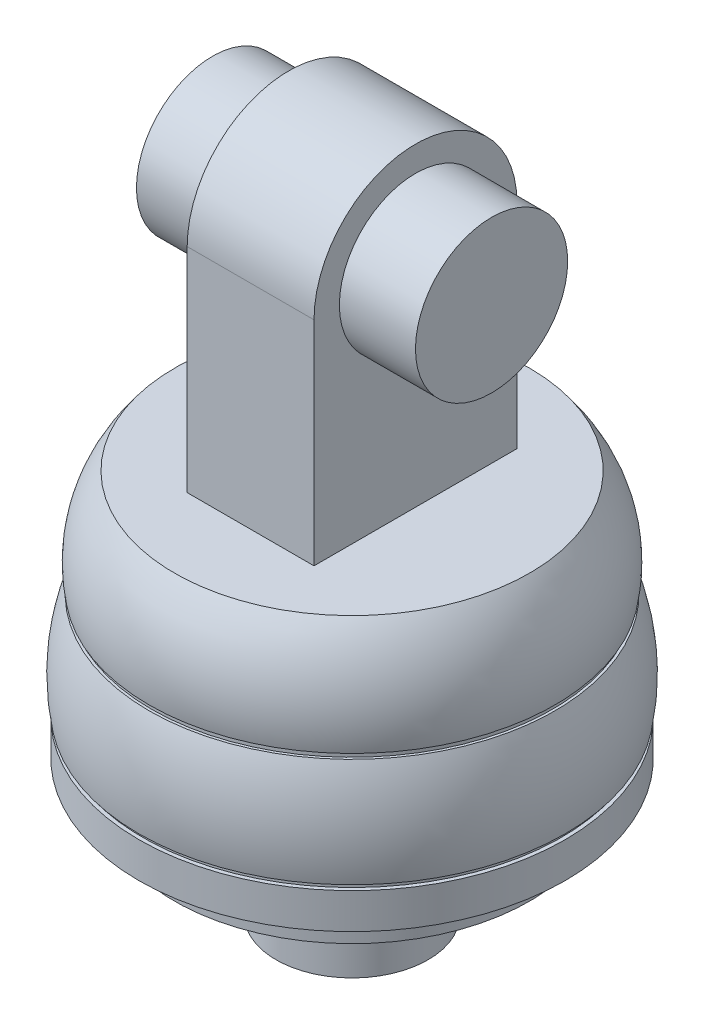
SolidWorks part; units mm, degrees
ref_plane "Front Plane" through (0, 0, 0) normal (0, 0, 1) x (1, 0, 0)
ref_plane "Top Plane" through (0, 0, 0) normal (0, 1, 0) x (1, 0, 0)
ref_plane "Right Plane" through (0, 0, 0) normal (1, 0, 0) x (0, 0, -1)
sketch "Sketch1" plane through (0, 0, 0) normal (0, 0, 1) x (1, 0, 0)
  line L0 (0, 0) -> (0, 20)
  line L1 (0, 20) -> (-35, 20)
  line L2 (0, 0) -> (-40, 0)
  arc A0 (-35, 20) -> (-40, 0) centre (-15.404, 4.476) ccw
  dimension "D4" = 25
  dimension "D1" = 20
  dimension "D2" = 35
  dimension "D3" = 40
revolve "Revolve1" add sketch "Sketch1" angle 360 about L0
sketch "Sketch2" plane through (0, 0, 0) normal (0, -1, 0) x (1, 0, 0)
  circle A0 centre (0, 0) radius 39.5
  dimension "D1" = 79
extrude "Boss-Extrude1" add sketch "Sketch2" along normal blind 1
sketch "Sketch3" plane through (0, 0, 0) normal (1, 0, 0) x (0, 0, -1)
  line L0 (-40, -1) -> (0, -1)
  line L1 (-39.5, -1) -> (39.5, -1) construction
  line L2 (0, -1) -> (0, -21)
  line L3 (0, -21) -> (-42, -21)
  arc A0 (-40, -1) -> (-42, -21) centre (-5.5677, -14.5432) ccw
  dimension "D4" = 37
  dimension "D1" = 42
  dimension "D2" = 20
  dimension "D3" = 40
revolve "Revolve2" add sketch "Sketch3" angle 360 about L2
sketch "Sketch4" plane through (0, -21, 0) normal (0, -1, 0) x (1, 0, 0)
  circle A0 centre (0, 0) radius 41.25
  dimension "D1" = 82.5
extrude "Boss-Extrude2" add sketch "Sketch4" along normal blind 1
sketch "Sketch5" plane through (0, -22, 0) normal (0, -1, 0) x (1, 0, 0)
  circle A0 centre (0, 0) radius 42
  dimension "D1" = 84
extrude "Boss-Extrude3" add sketch "Sketch5" along normal blind 7
sketch "Sketch6" plane through (0, -29, 0) normal (0, -1, 0) x (1, 0, 0)
  circle A0 centre (0, 0) radius 35
  dimension "D1" = 70
extrude "Boss-Extrude4" add sketch "Sketch6" along normal blind 7
sketch "Sketch7" plane through (0, -36, 0) normal (0, -1, 0) x (1, 0, 0)
  circle A0 centre (0, 0) radius 15
  dimension "D1" = 30
extrude "Boss-Extrude5" add sketch "Sketch7" along normal blind 20
sketch "Sketch8" plane through (0, 20, 0) normal (0, 1, 0) x (1, 0, 0)
  line L1 (-12.5, -20) -> (12.5, -20)
  line L2 (-12.5, -20) -> (-12.5, 20)
  line L3 (-12.5, 20) -> (12.5, 20)
  line L4 (12.5, -20) -> (12.5, 20)
  line L5 (-12.5, -20) -> (12.5, 20) construction
  line L6 (-12.5, 20) -> (12.5, -20) construction
  point P0 (0, 0)
  dimension "D1" = 25
  dimension "D2" = 40
extrude "Boss-Extrude6" add sketch "Sketch8" along normal blind 42
sketch "Sketch10" plane through (0, 0, 0) normal (1, 0, 0) x (0, 0, -1)
  line L0 (20, 62) -> (-20, 62)
  arc A0 (20, 62) -> (-20, 62) centre (0, 62) ccw
  dimension "D1" = 20
extrude "Boss-Extrude7" add sketch "Sketch10" along normal mid plane 25
sketch "Sketch11" plane through (-12.5, 0, 0) normal (-1, 0, 0) x (0, 0, 1)
  circle A0 centre (0, 62) radius 15
  dimension "D1" = 30
extrude "Boss-Extrude8" add sketch "Sketch11" along normal blind 15 separate body
sketch "Sketch12" plane through (12.5, 0, 0) normal (1, 0, 0) x (0, 0, -1)
  circle A0 centre (0, 62) radius 15
  dimension "D1" = 30
extrude "Boss-Extrude9" add sketch "Sketch12" along normal blind 15
